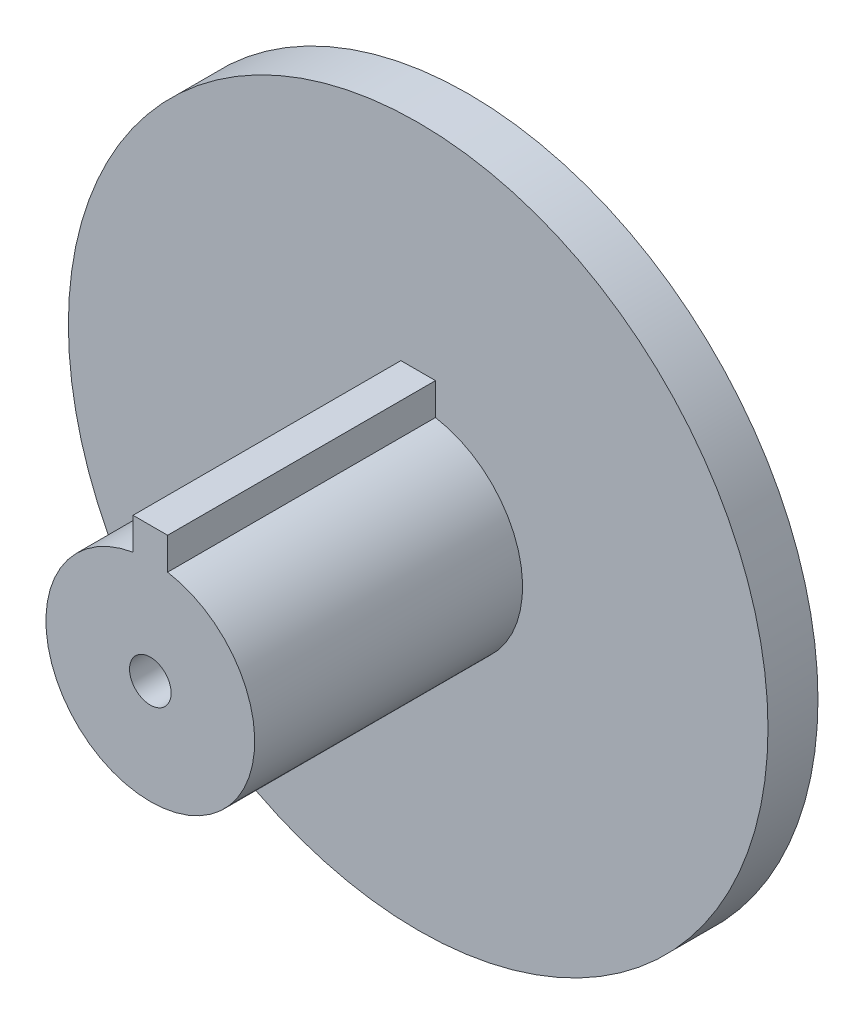
SolidWorks part; units mm, degrees
ref_plane "Front Plane" through (0, 0, 0) normal (0, 0, 1) x (1, 0, 0)
ref_plane "Top Plane" through (0, 0, 0) normal (0, 1, 0) x (1, 0, 0)
ref_plane "Right Plane" through (0, 0, 0) normal (1, 0, 0) x (0, 0, -1)
sketch "Sketch1" plane through (0, 0, 0) normal (0, 0, 1) x (1, 0, 0)
  circle A0 centre (0, 0) radius 44.45
  dimension "D1" = 88.9
extrude "Boss-Extrude1" add sketch "Sketch1" along normal blind 6.35 contours A0
sketch "Sketch2" plane through (0, 0, 6.35) normal (0, 0, 1) x (1, 0, 0)
  line L0 (0, 17.145) -> (0, 13.5382) construction
  line L1 (-2.1971, 17.145) -> (2.1971, 17.145)
  line L2 (-2.1971, 17.145) -> (-2.1971, 13.081)
  line L4 (2.1971, 17.145) -> (2.1971, 13.081)
  arc A1 (-2.1971, 13.081) -> (2.1971, 13.081) centre (0, 0) ccw
  dimension "D1" = 17.145
  dimension "D2" = 0
  dimension "D4" = 4.064
  dimension "D5" = 4.3942
extrude "Boss-Extrude4" add sketch "Sketch2" along normal blind 34.036
sketch "Sketch3" plane through (0, 0, 0) normal (0, 0, -1) x (-1, 0, 0)
  circle A0 centre (0, 0) radius 2.6416
  dimension "D1" = 5.2832
extrude "Cut-Extrude1" cut sketch "Sketch3" against normal through all
equation "\"width_of_film\"= 1.5'a lil more than 35mm"
